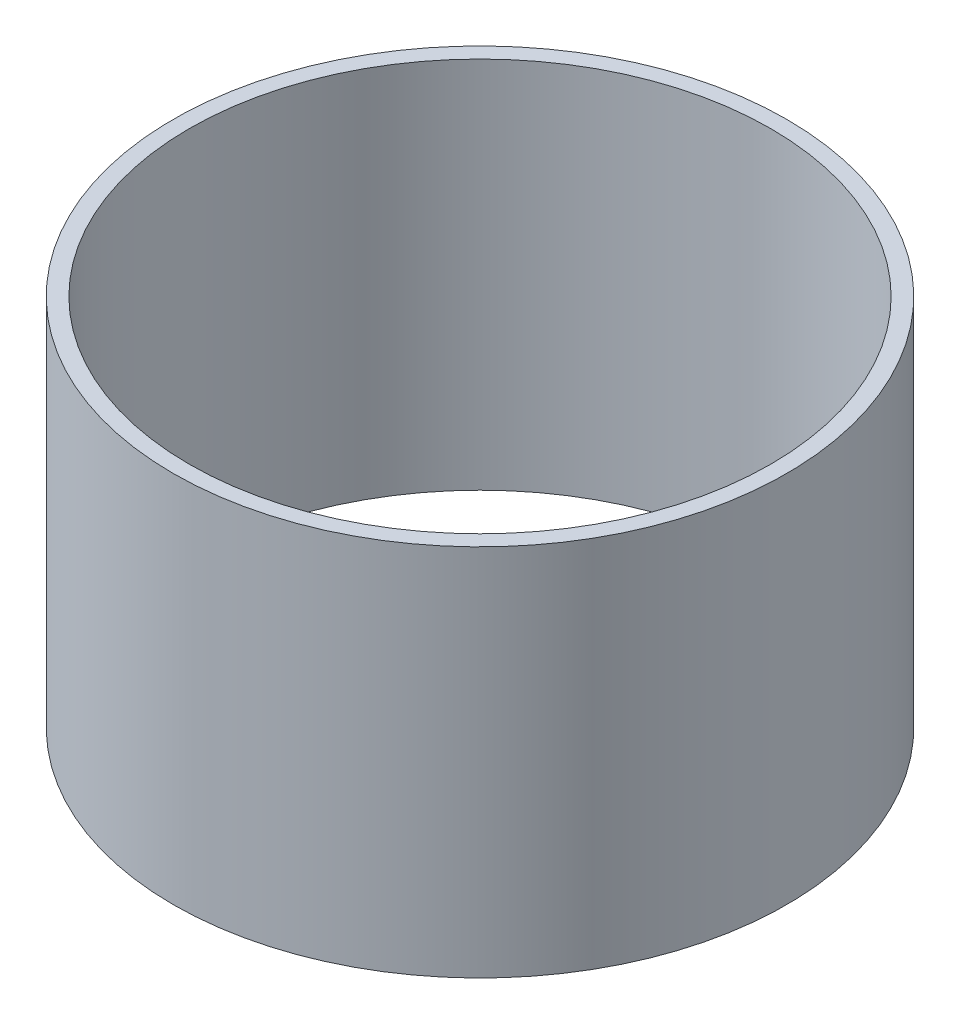
SolidWorks part; units mm, degrees
ref_plane "Front Plane" through (0, 0, 0) normal (0, 0, 1) x (1, 0, 0)
ref_plane "Top Plane" through (0, 0, 0) normal (0, 1, 0) x (1, 0, 0)
ref_plane "Right Plane" through (0, 0, 0) normal (1, 0, 0) x (0, 0, -1)
sketch "Sketch1" plane through (0, 0, 0) normal (0, 1, 0) x (1, 0, 0)
  circle A0 centre (0, 0) radius 54.5
  circle A1 centre (0, 0) radius 57.5
  dimension "D1" = 109
  dimension "D2" = 3
extrude "Boss-Extrude1" add sketch "Sketch1" along normal blind 70
sketch "Sketch2" plane through (-168.9329, 99.4365, -468.1144) normal (0, 0, 1) x (1, 0, 0)
  line L0 (111.4329, -29.4365) -> (111.4329, -99.4365) construction
  line L1 (111.4329, 150.5635) -> (226.4329, 150.5635) construction
  line L2 (111.4329, 150.5635) -> (111.4329, 50.5635) construction
  line L3 (111.4329, 50.5635) -> (226.4329, 50.5635) construction
  line L4 (226.4329, 150.5635) -> (226.4329, 50.5635) construction
  line L5 (226.4329, -99.4365) -> (226.4329, -29.4365) construction
  line L6 (118.4329, 143.5635) -> (118.4329, 57.5635)
  line L7 (118.4329, 57.5635) -> (219.4329, 57.5635)
  line L8 (219.4329, 143.5635) -> (219.4329, 57.5635)
  line L9 (118.4329, 143.5635) -> (219.4329, 143.5635)
  line L10 (111.4329, -99.4365) -> (226.4329, -99.4365) construction
  dimension "D2" = 250
  dimension "D3" = 100
  dimension "D1" = 7
